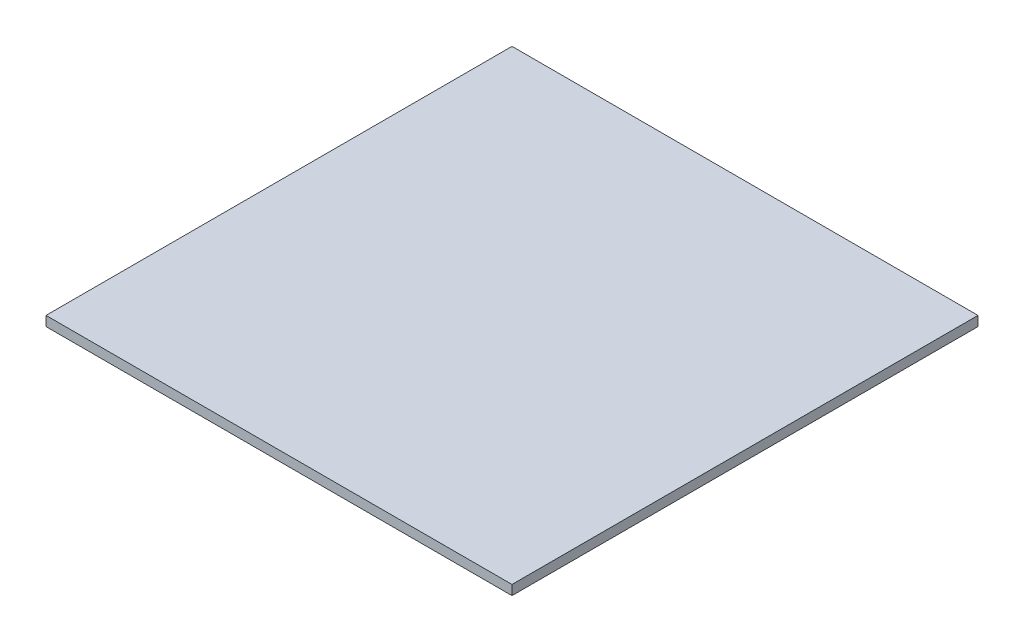
SolidWorks part; units mm, degrees
material "6061-T6 (SS)"
ref_plane "Front Plane" through (0, 0, 0) normal (0, 0, 1) x (1, 0, 0)
ref_plane "Top Plane" through (0, 0, 0) normal (0, 1, 0) x (1, 0, 0)
ref_plane "Right Plane" through (0, 0, 0) normal (1, 0, 0) x (0, 0, -1)
sketch "Sketch2" plane through (0, 0, 0) normal (0, 1, 0) x (1, 0, 0)
  line L1 (-152.4, -152.4) -> (152.4, -152.4)
  line L2 (-152.4, -152.4) -> (-152.4, 152.4)
  line L3 (-152.4, 152.4) -> (152.4, 152.4)
  line L4 (152.4, -152.4) -> (152.4, 152.4)
  line L5 (-152.4, -152.4) -> (152.4, 152.4) construction
  line L6 (-152.4, 152.4) -> (152.4, -152.4) construction
  point P0 (0, 0)
  dimension "D1" = 304.8
  dimension "D2" = 304.8
extrude "Boss-Extrude1" add sketch "Sketch2" along normal blind 6.35
